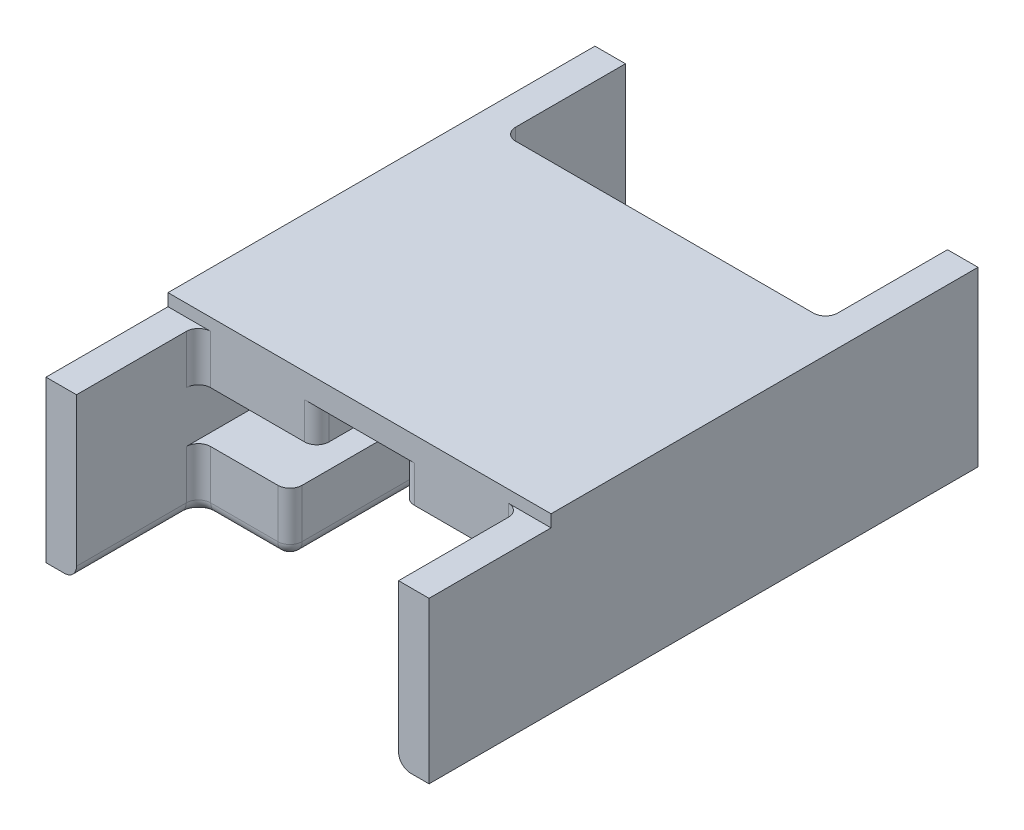
SolidWorks part; units mm, degrees
ref_plane "Front Plane" through (0, 0, 0) normal (0, 0, 1) x (1, 0, 0)
ref_plane "Top Plane" through (0, 0, 0) normal (0, 1, 0) x (1, 0, 0)
ref_plane "Right Plane" through (0, 0, 0) normal (1, 0, 0) x (0, 0, -1)
sketch "Sketch1" plane through (0, 0, 0) normal (0, 0, 1) x (1, 0, 0)
  line L1 (-35.5071, 10.5491) -> (-35.5071, -17.8009)
  line L2 (-35.5071, -17.8009) -> (-15.5071, -17.8009)
  line L3 (-15.5071, -17.8009) -> (-15.5071, -7.8009)
  line L4 (-15.5071, -7.8009) -> (-30.5071, -7.8009)
  line L5 (-30.5071, -7.8009) -> (-30.5071, 0.5491)
  line L6 (-30.5071, 0.5491) -> (-11.1071, 0.5491)
  line L7 (-4.1071, 10.5491) -> (-4.1071, -4.2151) construction
  line L8 (-35.5071, 10.5491) -> (27.2929, 10.5491)
  line L10 (2.8929, 6.5491) -> (-11.1071, 6.5491)
  line L11 (-11.1071, 6.5491) -> (-11.1071, 0.5491)
  line L12 (2.8929, 6.5491) -> (2.8929, 0.5491)
  line L13 (22.2929, 0.5491) -> (2.8929, 0.5491)
  line L14 (22.2929, -7.8009) -> (22.2929, 0.5491)
  line L15 (7.2929, -7.8009) -> (22.2929, -7.8009)
  line L16 (7.2929, -17.8009) -> (7.2929, -7.8009)
  line L17 (27.2929, -17.8009) -> (7.2929, -17.8009)
  line L18 (27.2929, 10.5491) -> (27.2929, -17.8009)
  dimension "D1" = 26.4
  dimension "D2" = 5
  dimension "D4" = 8.35
  dimension "D5" = 10
  dimension "D6" = 15
  dimension "D8" = 6
  dimension "D9" = 10
extrude "Boss-Extrude1" add sketch "Sketch1" against normal blind 50
ref_plane "Plane 1" through (0, 0, 0) normal (0, 0, 1) x (1, 0, 0)
sketch "Sketch2" plane through (0, 0, 0) normal (0, 0, 1) x (1, 0, 0)
  line L0 (-4.1071, 8.5491) -> (-4.1071, -1.4509) construction
  line L1 (-30.5071, -7.8009) -> (-30.5071, 0.5491) construction
  line L2 (-35.5071, 8.5491) -> (-30.5071, 8.5491)
  line L3 (-35.5071, 8.5491) -> (-35.5071, -17.8009)
  line L4 (-35.5071, -17.8009) -> (-30.5071, -17.8009)
  line L5 (-30.5071, 8.5491) -> (-30.5071, -17.8009)
  line L6 (-35.5071, 10.5491) -> (-35.5071, -17.8009) construction
  line L7 (27.2929, -17.8009) -> (22.2929, -17.8009)
  line L8 (22.2929, 8.5491) -> (22.2929, -17.8009)
  line L9 (27.2929, 8.5491) -> (22.2929, 8.5491)
  line L10 (27.2929, 8.5491) -> (27.2929, -17.8009)
  dimension "D1" = 0
  dimension "D2" = 0
extrude "Boss-Extrude2" add sketch "Sketch2" along normal blind 20 contours L3 L4 L5 L2 | L8 L7 L10 L9
ref_plane "Plane2" through (0, 0, -50) normal (0, 0, -1) x (-1, 0, 0)
sketch "Sketch4" plane through (0, 0, -50) normal (0, 0, -1) x (-1, 0, 0)
  line L0 (4.1071, 8.5491) -> (4.1071, -1.4509) construction
  line L21 (-27.2929, 10.5491) -> (-22.2929, 10.5491)
  line L22 (-27.2929, 10.5491) -> (-27.2929, -17.8009)
  line L23 (-27.2929, -17.8009) -> (-22.2929, -17.8009)
  line L24 (-22.2929, 10.5491) -> (-22.2929, -17.8009)
  line L25 (35.5071, 10.5491) -> (30.5071, 10.5491)
  line L26 (35.5071, 10.5491) -> (35.5071, -17.8009)
  line L27 (35.5071, -17.8009) -> (30.5071, -17.8009)
  line L28 (30.5071, 10.5491) -> (30.5071, -17.8009)
extrude "Boss-Extrude3" add sketch "Sketch4" along normal blind 20
fillet "Fillet2" radius 2 26 edges at (-30.5071, -12.8009, -50) (-30.5071, 5.5491, -50) (-30.5071, -17.8009, -60) (-30.5071, 4.5491, 0) (-30.5071, -17.8009, 10) (-23.0071, -17.8009, 0) (-15.5071, -12.8009, 0) (2.8929, 3.5491, 0) (-23.0071, -17.8009, -50) (-15.5071, -12.8009, -50) (2.8929, 3.5491, -50) (-15.5071, -17.8009, -25) (-30.5071, -12.8009, 0) (-11.1071, 3.5491, -50) (-11.1071, 3.5491, 0) (7.2929, -12.8009, -50) (7.2929, -17.8009, -25) (7.2929, -12.8009, 0) (22.2929, -17.8009, 10) (14.7929, -17.8009, 0) (22.2929, -12.8009, 0) (22.2929, 4.5491, 0) (22.2929, 5.5491, -50) (22.2929, -12.8009, -50) (22.2929, -17.8009, -60) (14.7929, -17.8009, -50)
